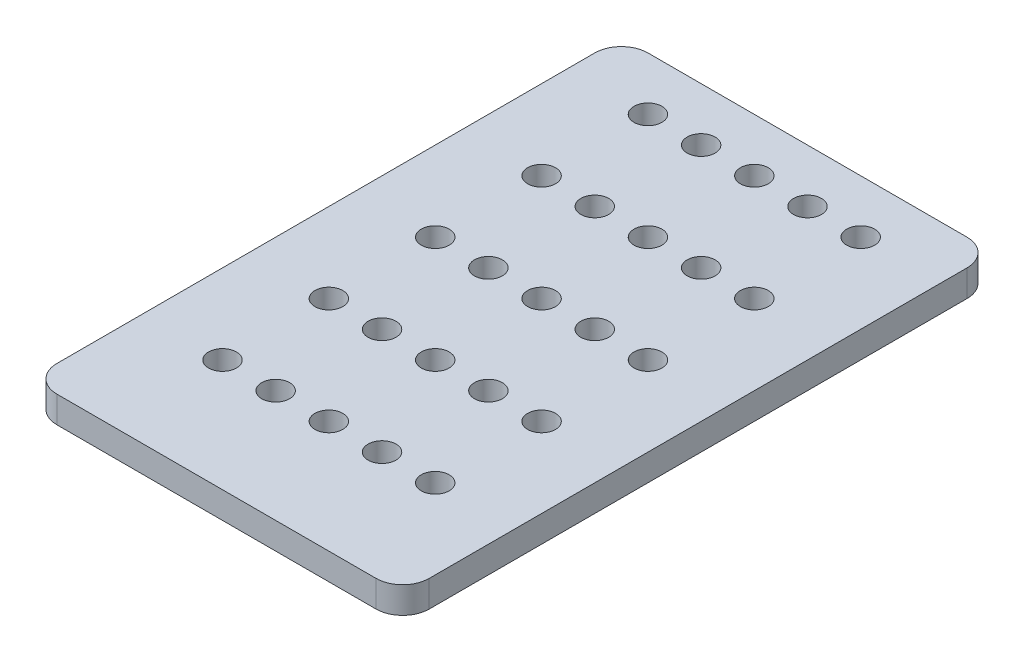
SolidWorks part; units mm, degrees
ref_plane "Front Plane" through (0, 0, 0) normal (0, 0, 1) x (1, 0, 0)
ref_plane "Top Plane" through (0, 0, 0) normal (0, 1, 0) x (1, 0, 0)
ref_plane "Right Plane" through (0, 0, 0) normal (1, 0, 0) x (0, 0, -1)
sketch "Sketch1" plane through (0, 0, 0) normal (0, 1, 0) x (1, 0, 0)
  line L0 (16, 0) -> (-16, 0) construction
  line L2 (-28, 8) -> (28, 8)
  line L3 (-28, 8) -> (-28, -80.9)
  line L4 (-28, -80.9) -> (28, -80.9)
  line L5 (28, 8) -> (28, -80.9)
  line L6 (0, -80.9) -> (0, 8) construction
  line L7 (-28, -36.45) -> (28, -36.45) construction
  circle A0 centre (-16, 0) radius 2.1
  circle A1 centre (16, 0) radius 2.1
  circle A2 centre (-8, 0) radius 2.1
  circle A3 centre (0, 0) radius 2.1
  circle A4 centre (8, 0) radius 2.1
  circle A5 centre (-16, -16) radius 2.1
  circle A6 centre (-8, -16) radius 2.1
  circle A7 centre (0, -16) radius 2.1
  circle A8 centre (8, -16) radius 2.1
  circle A9 centre (16, -16) radius 2.1
  circle A10 centre (-16, -32) radius 2.1
  circle A11 centre (-8, -32) radius 2.1
  circle A12 centre (0, -32) radius 2.1
  circle A13 centre (8, -32) radius 2.1
  circle A14 centre (16, -32) radius 2.1
  circle A15 centre (-16, -48) radius 2.1
  circle A16 centre (-8, -48) radius 2.1
  circle A17 centre (0, -48) radius 2.1
  circle A18 centre (8, -48) radius 2.1
  circle A19 centre (16, -48) radius 2.1
  circle A20 centre (-16, -64) radius 2.1
  circle A21 centre (-8, -64) radius 2.1
  circle A22 centre (0, -64) radius 2.1
  circle A23 centre (8, -64) radius 2.1
  circle A24 centre (16, -64) radius 2.1
  point P8 (0, 0)
  point P277 (0, -36.45)
  dimension "D1" = 4.2
  dimension "D2" = 32
  dimension "D3" = 8
  dimension "D4" = 12
  dimension "D5" = 88.9
  dimension "D6" = 4
  dimension "D7" = 5
extrude "Boss-Extrude1" add sketch "Sketch1" along normal blind 4
fillet "Fillet1" radius 4 4 edges at (-28, 2, 80.9) (28, 2, 80.9) (28, 2, -8) (-28, 2, -8)
